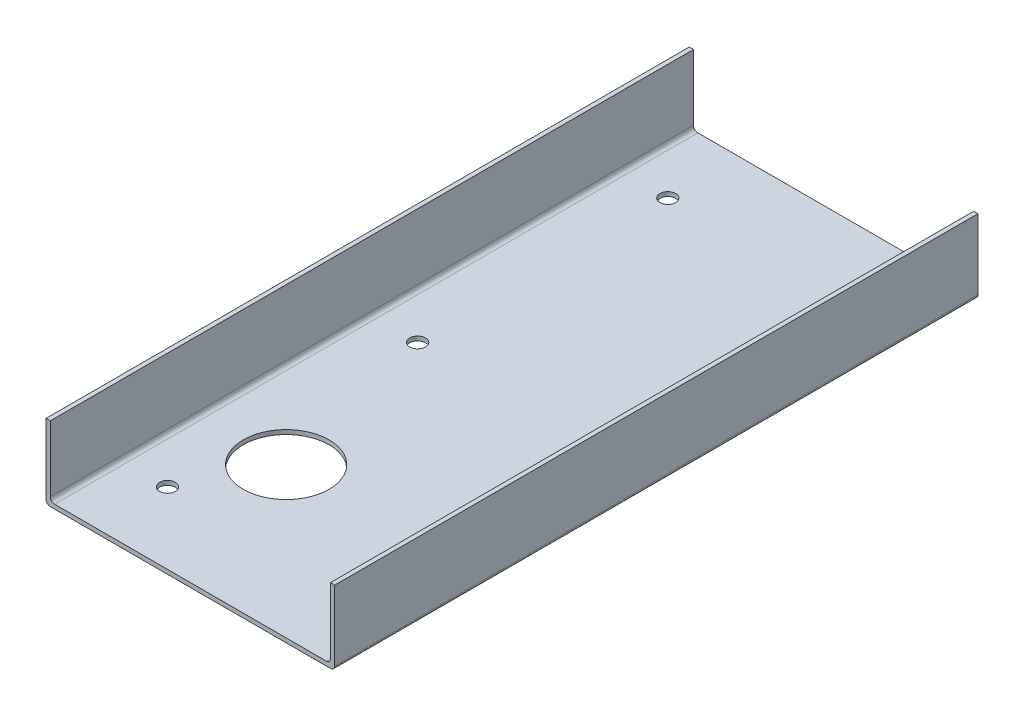
SolidWorks part; units mm, degrees
material "1.0490 (S275N)"
ref_plane "Front Plane" through (0, 0, 0) normal (0, 0, 1) x (1, 0, 0)
ref_plane "Top Plane" through (0, 0, 0) normal (0, 1, 0) x (1, 0, 0)
ref_plane "Right Plane" through (0, 0, 0) normal (1, 0, 0) x (0, 0, -1)
sketch "Sketch1" plane through (0, 0, 0) normal (0, 0, 1) x (1, 0, 0)
  line L0 (-96.4001, 31.9882) -> (-96.4001, -14.0118)
  line L1 (-93.4001, -17.0118) -> (96.5999, -17.0118)
  line L2 (99.5999, -14.0118) -> (99.5999, 31.9882)
  line L3 (-99.4001, 31.9882) -> (-99.4001, -17.0118)
  line L4 (-96.4001, -20.0118) -> (99.5999, -20.0118)
  line L5 (102.5999, -17.0118) -> (102.5999, 31.9882)
  line L6 (-96.4001, -17.0118) -> (99.5999, -17.0118) construction
  line L7 (-96.4001, 31.9882) -> (-96.4001, -17.0118) construction
  line L8 (99.5999, -17.0118) -> (99.5999, 31.9882) construction
  line L9 (-99.4001, -20.0118) -> (102.5999, -20.0118) construction
  line L10 (-99.4001, 31.9882) -> (-99.4001, -20.0118) construction
  line L11 (102.5999, -20.0118) -> (102.5999, 31.9882) construction
  line L12 (-99.4001, 31.9882) -> (-96.4001, 31.9882)
  line L13 (99.5999, 31.9882) -> (102.5999, 31.9882)
  arc A0 (-93.4001, -17.0118) -> (-96.4001, -14.0118) centre (-93.4001, -14.0118) cw
  arc A1 (96.5999, -17.0118) -> (99.5999, -14.0118) centre (96.5999, -14.0118) ccw
  arc A2 (-96.4001, -20.0118) -> (-99.4001, -17.0118) centre (-96.4001, -17.0118) cw
  arc A3 (102.5999, -17.0118) -> (99.5999, -20.0118) centre (99.5999, -17.0118) cw
  dimension "D2" = 3
  dimension "D3" = 3
  dimension "D4" = 3
  dimension "D5" = 3
  dimension "D1" = 3
extrude "Boss-Extrude1" add sketch "Sketch1" along normal blind 450 contours L13 L5 A3 L4 A2 L3 L12 L0 A0 L1 A1 L2
extrude "Cut-Extrude2" cut sketch "Sketch3" against normal through all
sketch "Sketch3" plane through (-323.6983, -20.0118, 19.5447) normal (0, -1, 0) x (0, 0, -1)
  circle A0 centre (-325.4553, 287.2982) radius 30
hole_wizard "M10 Clearance Slot1" positions "Sketch4" profile "Sketch5" size "M10" standard "ISO" slot yes end condition through all
sketch "Sketch4" plane through (-323.6983, -20.0118, 19.5447) normal (0, -1, 0) x (0, 0, -1)
  point P0 (-380.4553, 390.2982)
  point P2 (-205.4553, 390.2982)
  point P4 (-30.4553, 390.2982)
  point P6 (-30.4553, 259.2982)
  point P8 (-205.4553, 259.2982)
  point P10 (-380.4553, 259.2982)
  point P25 (-18.2475, 259.9307)
sketch "Sketch5" plane through (66.5999, -20.0118, 400) normal (1, 0, 0) x (0, 0, -1)
  line L0 (0, 0) -> (0, 52)
  line L1 (0, 52) -> (5.5, 52)
  line L2 (5.5, 52) -> (5.5, 0)
  line L3 (5.5, 0) -> (0, 0)
  line L4 (0, -6.35) -> (0, 107.95) construction
  dimension "Thru Hole Dia." = 11
  dimension "Thru Hole Depth" = 52
ref_plane "Plane1" through (-96.4001, -20.0118, 450) normal (0, 0, -1) x (-1, 0, 0)
extrude "Cut-Extrude-Thin4" cut sketch "Sketch9" against normal blind 0.1 and the other way through all thin thin type one direction wall 0.1
sketch "Sketch9" plane through (-323.6983, -20.0118, 19.5447) normal (0, -1, 0) x (0, 0, -1)
  line L0 (-256.2535, 262.6315) -> (-256.2535, 227.2982)
  line L2 (-256.2535, 262.6315) -> (-307.6874, 262.6315)
  line L3 (-307.6874, 262.6315) -> (-307.6874, 227.2982)
extrude "Cut-Extrude-Thin5" cut sketch "Sketch10" against normal blind 0.1 and the other way through all thin thin type one direction wall 0.1
sketch "Sketch10" plane through (-323.6983, -20.0118, 19.5447) normal (0, -1, 0) x (0, 0, -1)
  line L0 (-120.6548, 262.7405) -> (-120.6548, 227.2982)
  line L3 (-120.6548, 262.7405) -> (-69.4778, 262.7405)
  line L4 (-69.4778, 262.7405) -> (-69.4778, 227.2982)
extrude "Cut-Extrude-Thin6" cut sketch "Sketch11" against normal blind 0.1 and the other way through all thin thin type one direction wall 0.1
sketch "Sketch11" plane through (-323.6983, -20.0118, 19.5447) normal (0, -1, 0) x (0, 0, -1)
  line L0 (-214.234, 403.6148) -> (-214.234, 423.2982)
  line L2 (-214.234, 403.6148) -> (-162.7917, 403.6148)
  line L3 (-162.7917, 403.6148) -> (-162.7917, 423.2982)
